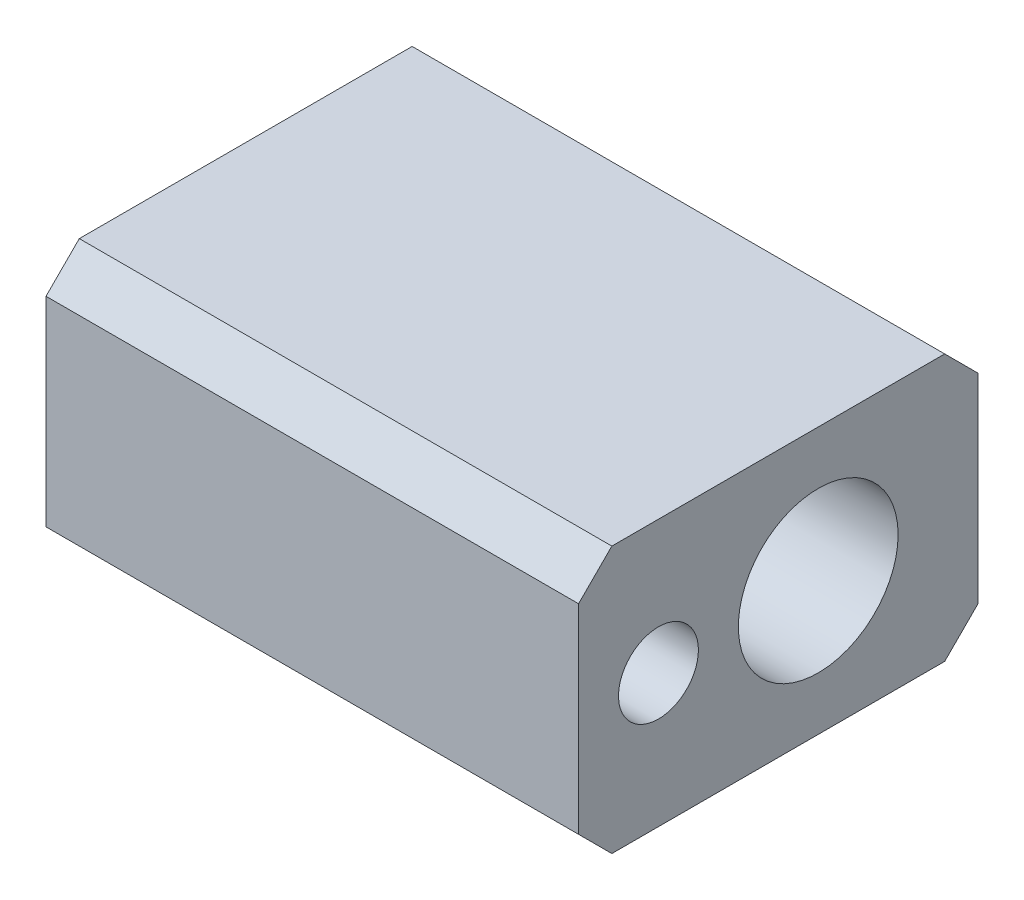
SolidWorks part; units mm, degrees
ref_plane "Front Plane" through (0, 0, 0) normal (1, 0, 0) x (0, 1, 0)
ref_plane "Top Plane" through (0, 0, 0) normal (0, 0, 1) x (0, 1, 0)
ref_plane "Right Plane" through (0, 0, 0) normal (0, 1, 0) x (-1, 0, 0)
sketch "Sketch1" plane through (0, 0, 0) normal (1, 0, 0) x (0, 1, 0)
  line L0 (0, -41.91) -> (0, 41.91) construction
  line L1 (25.4, -38.1) -> (-25.4, -38.1)
  line L2 (25.4, -38.1) -> (25.4, 38.1)
  line L3 (25.4, 38.1) -> (-25.4, 38.1)
  line L4 (-25.4, -38.1) -> (-25.4, 38.1)
  line L5 (25.4, -38.1) -> (-25.4, 38.1) construction
  line L6 (25.4, 38.1) -> (-25.4, -38.1) construction
  circle A0 centre (0, -7.62) radius 15.24
  circle A1 centre (0, 22.86) radius 7.62
  point P0 (0, 0)
  dimension "D3" = 30.48
  dimension "D5" = 15.24
  dimension "D1" = 50.8
  dimension "D2" = 76.2
  dimension "D4" = 30.48
  dimension "D6" = 15.24
extrude "Boss-Extrude1" add sketch "Sketch1" along normal blind 101.6
fillet "Chamfer2" radius 6.35 2 edges at (50.8, -25.4, -38.1) (50.8, -25.4, 38.1) profile chamfer
chamfer "Chamfer1" distance 6.35 angle 45 2 edges at (50.8, 25.4, -38.1) (50.8, 25.4, 38.1)
